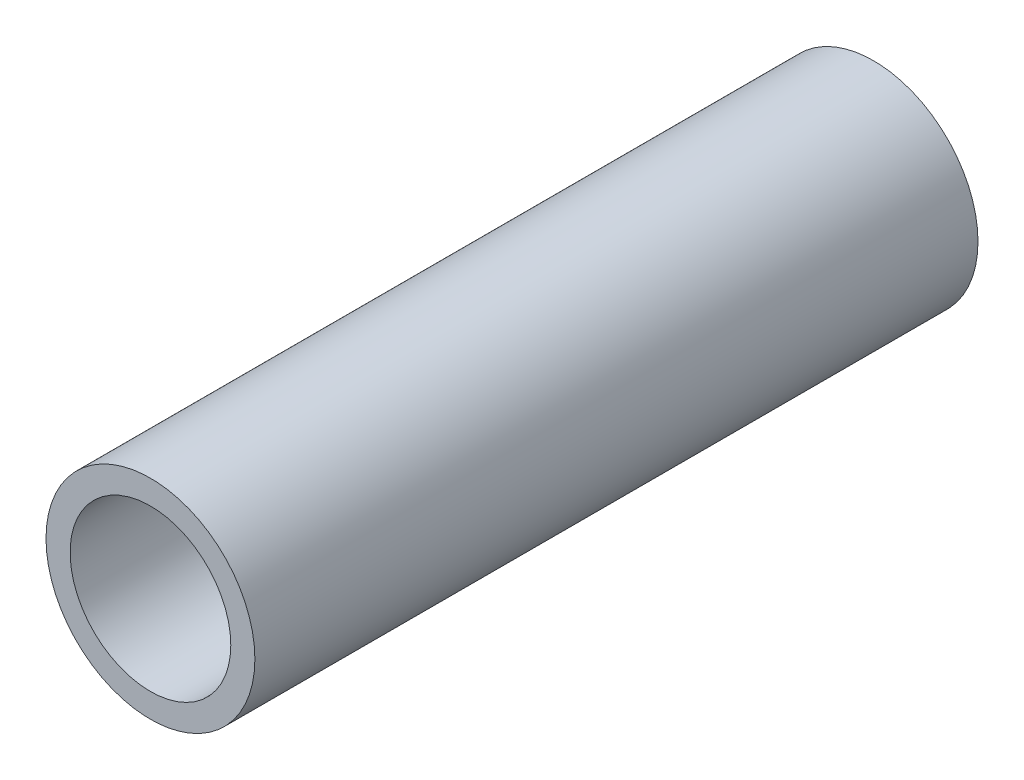
SolidWorks part; units mm, degrees
ref_plane "Front Plane" through (0, 0, 0) normal (0, 0, 1) x (1, 0, 0)
ref_plane "Top Plane" through (0, 0, 0) normal (0, 1, 0) x (1, 0, 0)
ref_plane "Right Plane" through (0, 0, 0) normal (1, 0, 0) x (0, 0, -1)
sketch "Sketch1" plane through (0, 0, 0) normal (0, 0, 1) x (1, 0, 0)
  circle A0 centre (0, 0) radius 16.51
  circle A1 centre (0, 0) radius 12.7
  dimension "D1" = 33.02
  dimension "D2" = 25.4
extrude "Boss-Extrude1" add sketch "Sketch1" along normal blind 114.3
ref_plane "Fitting2" through (0, 0, 114.3) normal (0, 0, 1) x (1, 0, 0)
ref_plane "Fitting1" through (0, 0, 0) normal (0, 0, 1) x (1, 0, 0)
